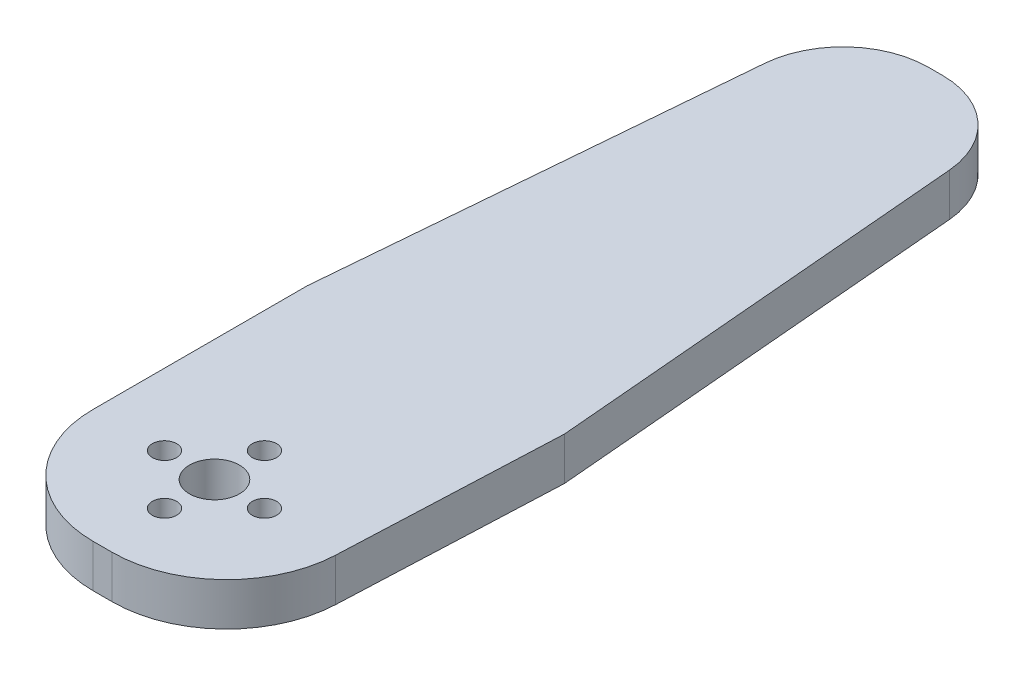
SolidWorks part; units mm, degrees
ref_plane "Front Plane" through (0, 0, 0) normal (0, 0, 1) x (1, 0, 0)
ref_plane "Top Plane" through (0, 0, 0) normal (0, 1, 0) x (1, 0, 0)
ref_plane "Right Plane" through (0, 0, 0) normal (1, 0, 0) x (0, 0, -1)
ref_plane "PY_m6_000" through (0, -6, 0) normal (0, 1, 0) x (1, 0, 0)
sketch "S_prism1" plane through (0, -6, 0) normal (0, 1, 0) x (1, 0, 0)
  line L0 (-1, -16) -> (1.6805, -16)
  line L1 (17.6654, -0.695) -> (19, 30)
  line L2 (19, 30) -> (13.9407, 89.0248)
  line L3 (1.9846, 100) -> (0.0154, 100)
  line L4 (-11.9407, 89.0248) -> (-17, 30)
  line L5 (-17, 30) -> (-17, 0)
  arc A0 (-17, 0) -> (-1, -16) centre (-1, 0) ccw
  arc A1 (1.6805, -16) -> (17.6654, -0.695) centre (1.6805, 0) ccw
  arc A2 (13.9407, 89.0248) -> (1.9846, 100) centre (1.9846, 88) ccw
  arc A3 (0.0154, 100) -> (-11.9407, 89.0248) centre (0.0154, 88) ccw
extrude "Boss_1" add sketch "S_prism1" along normal blind 6
ref_plane "PY_m8_000" through (0, -8, 0) normal (0, 1, 0) x (1, 0, 0)
sketch "S_cyl2" plane through (0, -8, 0) normal (0, 1, 0) x (1, 0, 0)
  circle A0 centre (0, 0) radius 12.5
  dimension "D1_S_cyl2" = 25
extrude "Boss_2" add sketch "S_cyl2" along normal blind 2
ref_plane "PY_m8_100" through (0, -8.1, 0) normal (0, 1, 0) x (1, 0, 0)
sketch "S_hole3" plane through (0, -8.1, 0) normal (0, 1, 0) x (1, 0, 0)
  circle A0 centre (0, 0) radius 3.5
  dimension "D1_S_hole3" = 7
extrude "Hole_3" cut sketch "S_hole3" along normal blind 8.2
sketch "S_hole4" plane through (0, -8.1, 0) normal (0, 1, 0) x (1, 0, 0)
  circle A0 centre (7, 0) radius 1.7
  dimension "D1_S_hole4" = 3.4
  dimension "P2" = 7
extrude "Hole_4" cut sketch "S_hole4" along normal blind 8.2
sketch "S_hole5" plane through (0, -8.1, 0) normal (0, 1, 0) x (1, 0, 0)
  circle A0 centre (0, -7) radius 1.7
  dimension "D1_S_hole5" = 3.4
  dimension "P2" = 7
extrude "Hole_5" cut sketch "S_hole5" along normal blind 8.2
sketch "S_hole6" plane through (0, -8.1, 0) normal (0, 1, 0) x (1, 0, 0)
  circle A0 centre (-7, 0) radius 1.7
  dimension "D1_S_hole6" = 3.4
  dimension "P2" = 7
extrude "Hole_6" cut sketch "S_hole6" along normal blind 8.2
sketch "S_hole7" plane through (0, -8.1, 0) normal (0, 1, 0) x (1, 0, 0)
  circle A0 centre (0, 7) radius 1.7
  dimension "D1_S_hole7" = 3.4
  dimension "P2" = 7
extrude "Hole_7" cut sketch "S_hole7" along normal blind 8.2
sketch "S_hole8" plane through (0, -8.1, 0) normal (0, 1, 0) x (1, 0, 0)
  circle A0 centre (7, 0) radius 3.2
  dimension "D1_S_hole8" = 6.4
  dimension "P2" = 7
extrude "Hole_8" cut sketch "S_hole8" along normal blind 5.1
sketch "S_hole9" plane through (0, -8.1, 0) normal (0, 1, 0) x (1, 0, 0)
  circle A0 centre (0, -7) radius 3.2
  dimension "D1_S_hole9" = 6.4
  dimension "P2" = 7
extrude "Hole_9" cut sketch "S_hole9" along normal blind 5.1
sketch "S_hole10" plane through (0, -8.1, 0) normal (0, 1, 0) x (1, 0, 0)
  circle A0 centre (-7, 0) radius 3.2
  dimension "D1_S_hole10" = 6.4
  dimension "P2" = 7
extrude "Hole_10" cut sketch "S_hole10" along normal blind 5.1
sketch "S_hole11" plane through (0, -8.1, 0) normal (0, 1, 0) x (1, 0, 0)
  circle A0 centre (0, 7) radius 3.2
  dimension "D1_S_hole11" = 6.4
  dimension "P2" = 7
extrude "Hole_11" cut sketch "S_hole11" along normal blind 5.1
equation "\"plate_t\" = 3"
equation "\"clearance\" = 0.5"
